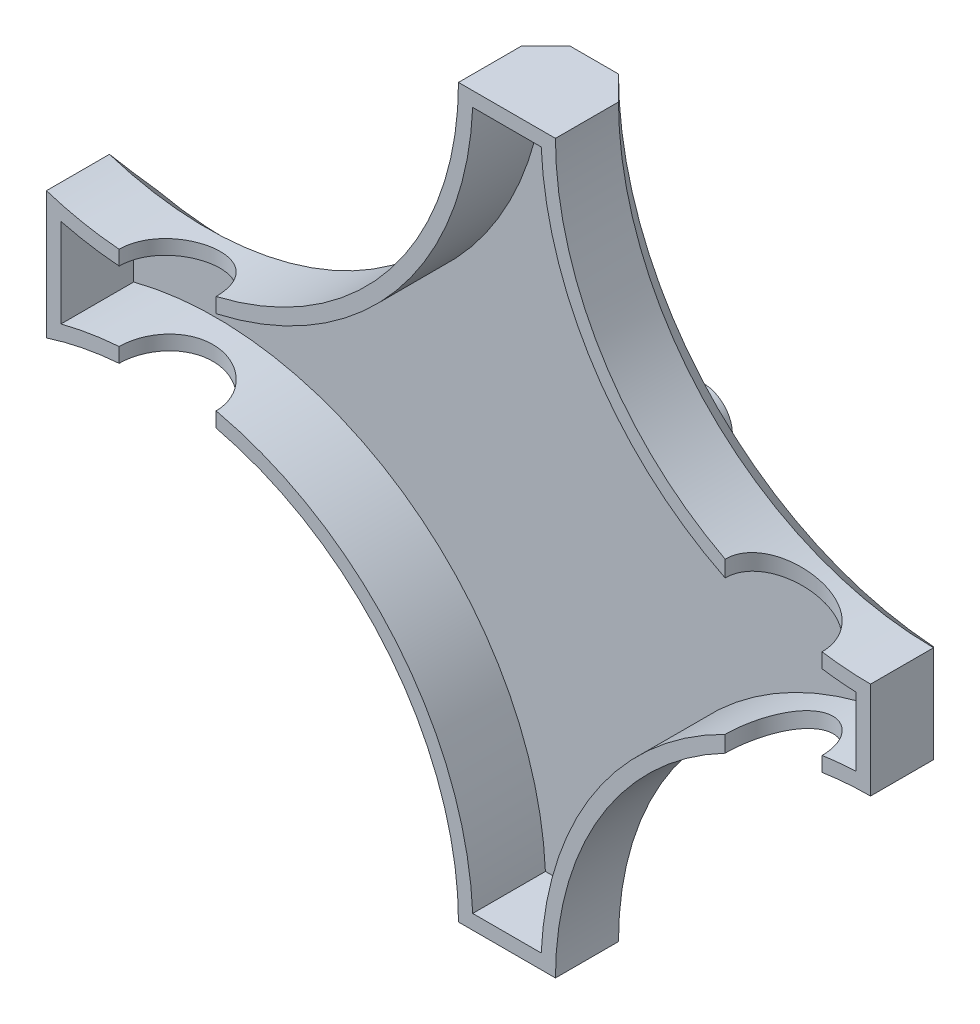
SolidWorks part; units mm, degrees
ref_plane "Front Plane" through (0, 0, 0) normal (0, 0, 1) x (1, 0, 0)
ref_plane "Top Plane" through (0, 0, 0) normal (0, 1, 0) x (1, 0, 0)
ref_plane "Right Plane" through (0, 0, 0) normal (1, 0, 0) x (0, 0, -1)
sketch "Sketch1" plane through (0, 0, 0) normal (0, 0, 1) x (1, 0, 0)
  line L1 (85, -75) -> (-85, -75)
  line L2 (85, -75) -> (85, 75)
  line L3 (85, 75) -> (-85, 75)
  line L4 (-85, -75) -> (-85, 75)
  line L5 (85, -75) -> (-85, 75) construction
  line L6 (85, 75) -> (-85, -75) construction
  point P0 (0, 0)
  dimension "D1" = 150
  dimension "D2" = 170
extrude "Boss-Extrude1" add sketch "Sketch1" along normal blind 18
sketch "Sketch2" plane through (0, 0, 0) normal (0, 0, -1) x (-1, 0, 0)
  line L0 (-151.6767, 0) -> (198.4978, 0) construction
  line L1 (0, 112.9215) -> (0, -139.2829) construction
  line L2 (-85, 75) -> (85, 75) construction
  line L3 (85, -75) -> (-85, -75) construction
  circle A0 centre (-85, 75) radius 65
  circle A1 centre (-85, -75) radius 65
  circle A2 centre (65, 75) radius 65
  circle A3 centre (65, -75) radius 65
  dimension "D1" = 130
  dimension "D2" = 130
  dimension "D5" = 130
  dimension "D6" = 130
  dimension "D3" = 65
  dimension "D4" = 65
extrude "Cut-Extrude1" cut sketch "Sketch2" against normal blind 20
shell "Shell2" thickness 3
sketch "Sketch3" plane through (0, 0, 0) normal (0, 1, 0) x (1, 0, 0)
  line L0 (-85, -18) -> (0, -18) construction
  line L1 (20, -18) -> (85, -18) construction
  circle A0 centre (-60, -18) radius 10
  circle A1 centre (65, -18) radius 10
  dimension "D1" = 20
  dimension "D3" = 20
  dimension "D2" = 25
  dimension "D4" = 20
extrude "Cut-Extrude2" cut sketch "Sketch3" against normal blind 20 and the other way blind 20
sketch "Sketch4" plane through (0, 0, 0) normal (0, 0, -1) x (-1, 0, 0)
  line L0 (0, -75) -> (-20, -75) construction
  line L1 (-20, 75) -> (0, 75) construction
  circle A0 centre (-10, -67) radius 2.5
  circle A1 centre (-10, 67) radius 2.5
  dimension "D1" = 5
  dimension "D2" = 5
  dimension "D3" = 8
  dimension "D4" = 8
extrude "Cut-Extrude3" cut sketch "Sketch4" against normal blind 20
chamfer "Chamfer1" distance 5 angle 45 6 edges at (-26.7574, 22.4405, 0) (-26.7574, -22.4405, 0) (-85, 0, 0) (39.0381, 29.0381, 0) (39.0381, -29.0381, 0) (85, 0, 0)
sketch "Sketch5" plane through (0, 0, 0) normal (0, 0, -1) x (-1, 0, 0)
  line L5 (2.5, -12.5) -> (-10, 0) construction
  line L6 (-1.7426, 8.2574) -> (-18.2574, -8.2574) construction
  line L8 (-85, -10) -> (-85, 10) construction
  line L10 (-21.7485, 11.7485) -> (-22.5, 12.5) construction
  circle A1 centre (-22.5, 12.5) radius 6
  circle A2 centre (2.5, 12.5) radius 6
  circle A3 centre (2.5, -12.5) radius 6
  circle A4 centre (-22.5, -12.5) radius 6
  point P0 (-10, 0)
  dimension "D4" = 12
  dimension "D5" = 12
  dimension "D6" = 12
  dimension "D7" = 12
  dimension "D1" = 25
  dimension "D2" = 25
  dimension "D3" = 75
extrude "Boss-Extrude2" add sketch "Sketch5" along normal blind 10
